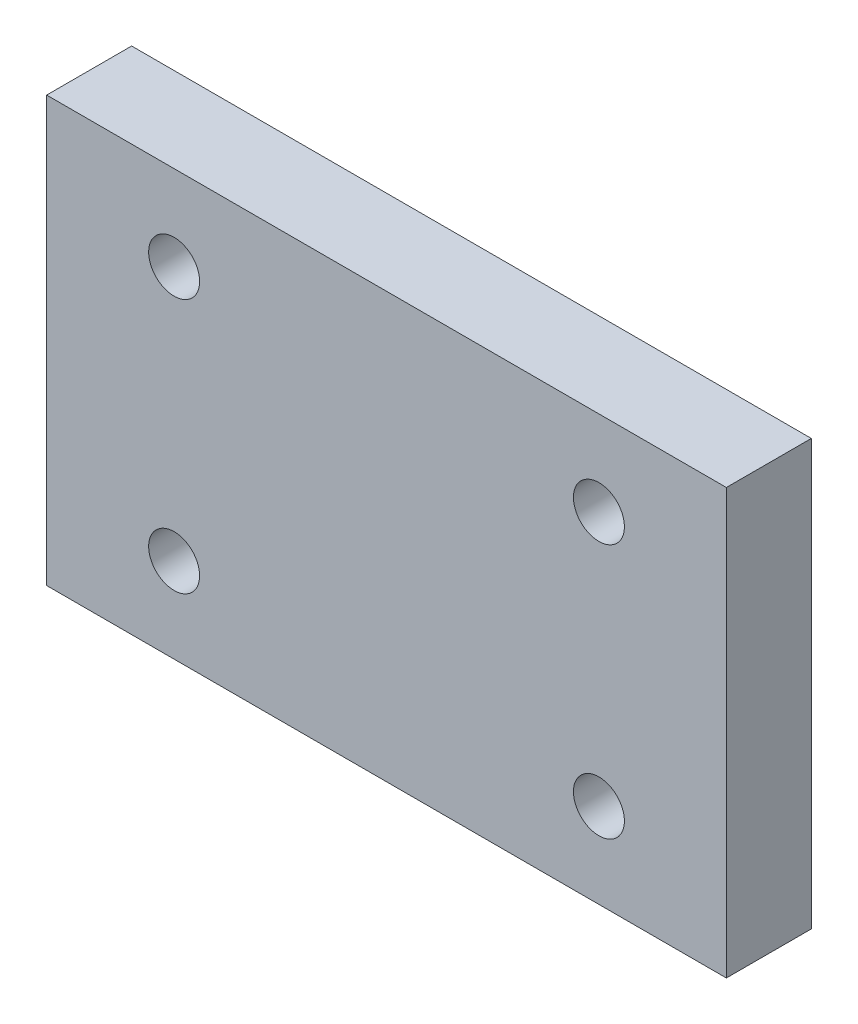
SolidWorks part; units mm, degrees
ref_plane "前视基准面" through (0, 0, 0) normal (0, 0, 1) x (1, 0, 0)
ref_plane "上视基准面" through (0, 0, 0) normal (0, 1, 0) x (1, 0, 0)
ref_plane "右视基准面" through (0, 0, 0) normal (1, 0, 0) x (0, 0, -1)
sketch "base" plane through (0, 0, 0) normal (0, 0, 1) x (1, 0, 0)
  line L1 (-40, -25) -> (40, -25)
  line L2 (-40, -25) -> (-40, 25)
  line L3 (-40, 25) -> (40, 25)
  line L4 (40, -25) -> (40, 25)
  line L5 (-40, -25) -> (40, 25) construction
  line L6 (-40, 25) -> (40, -25) construction
  point P0 (0, 0)
  dimension "宽度_0" = 80
  dimension "高度_0" = 50
extrude "block" add sketch "base" along normal blind 10
ref_plane "holes_钻孔轮廓草图_基准面" through (0, 0, 10) normal (0, 0, -1) x (-1, 0, 0)
sketch "holes_钻孔轮廓草图" plane through (0, 0, 10) normal (0, 0, -1) x (-1, 0, 0)
  circle A0 centre (25, 15) radius 3
  circle A1 centre (25, -15) radius 3
  circle A2 centre (-25, 15) radius 3
  circle A3 centre (-25, -15) radius 3
extrude "holes" cut sketch "holes_钻孔轮廓草图" along normal through all
